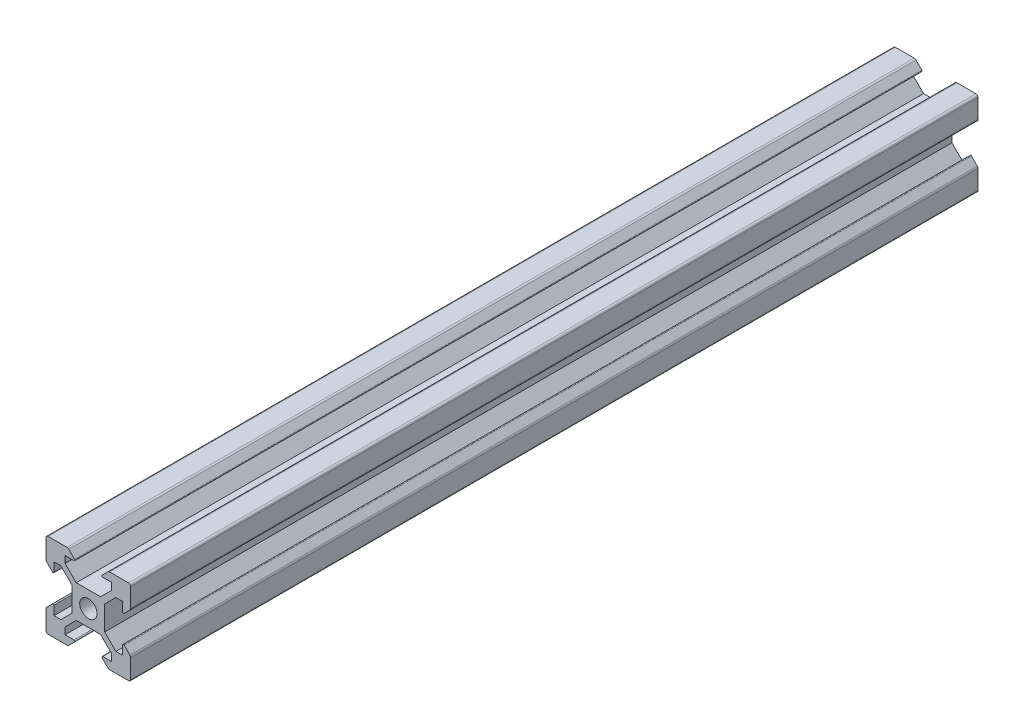
SolidWorks part; units mm, degrees
material "6063-T5"
ref_plane "Front Plane" through (0, 0, 0) normal (1, 0, 0) x (0, 1, 0)
ref_plane "Top Plane" through (0, 0, 0) normal (0, 0, 1) x (0, 1, 0)
ref_plane "Right Plane" through (0, 0, 0) normal (0, 1, 0) x (-1, 0, 0)
sketch "Sketch1" plane through (0, 0, 0) normal (0, 0, 1) x (0, 1, 0)
  line L0 (0, 0) -> (-10, 10) construction
  line L5 (-2.8601, -3.85) -> (2.8601, -3.85)
  line L6 (-3.85, -2.8601) -> (-3.85, 2.8601)
  line L11 (-2.8601, 3.85) -> (2.8601, 3.85)
  line L12 (3.85, -2.8601) -> (3.85, 2.8601)
  line L15 (-9.5, 10) -> (-5.0485, 10)
  line L16 (-4.6243, 9.8243) -> (-3.2414, 8.4414)
  line L17 (-3.3828, 8.1) -> (-5.5, 8.1)
  line L18 (-5.5, 8.1) -> (-5.5, 6.4899)
  line L19 (-5.5, 6.4899) -> (-2.8601, 3.85)
  line L20 (-6.4899, 5.5) -> (-3.85, 2.8601)
  line L21 (-10, 9.5) -> (-10, 5.0485)
  line L22 (-8.1, 5.5) -> (-6.4899, 5.5)
  line L23 (-8.1, 3.3828) -> (-8.1, 5.5)
  line L24 (-9.8243, 4.6243) -> (-8.4414, 3.2414)
  line L25 (10, 9.5) -> (10, 5.0485)
  line L26 (9.8243, 4.6243) -> (8.4414, 3.2414)
  line L27 (8.1, 3.3828) -> (8.1, 5.5)
  line L28 (8.1, 5.5) -> (6.4899, 5.5)
  line L29 (6.4899, 5.5) -> (3.85, 2.8601)
  line L30 (5.5, 6.4899) -> (2.8601, 3.85)
  line L31 (9.5, 10) -> (5.0485, 10)
  line L32 (5.5, 8.1) -> (5.5, 6.4899)
  line L33 (3.3828, 8.1) -> (5.5, 8.1)
  line L34 (4.6243, 9.8243) -> (3.2414, 8.4414)
  line L35 (9.5, -10) -> (5.0485, -10)
  line L36 (4.6243, -9.8243) -> (3.2414, -8.4414)
  line L37 (3.3828, -8.1) -> (5.5, -8.1)
  line L38 (5.5, -8.1) -> (5.5, -6.4899)
  line L39 (5.5, -6.4899) -> (2.8601, -3.85)
  line L40 (6.4899, -5.5) -> (3.85, -2.8601)
  line L41 (10, -9.5) -> (10, -5.0485)
  line L42 (8.1, -5.5) -> (6.4899, -5.5)
  line L43 (8.1, -3.3828) -> (8.1, -5.5)
  line L44 (9.8243, -4.6243) -> (8.4414, -3.2414)
  line L45 (-10, -9.5) -> (-10, -5.0485)
  line L46 (-9.8243, -4.6243) -> (-8.4414, -3.2414)
  line L47 (-8.1, -3.3828) -> (-8.1, -5.5)
  line L48 (-8.1, -5.5) -> (-6.4899, -5.5)
  line L49 (-6.4899, -5.5) -> (-3.85, -2.8601)
  line L50 (-5.5, -6.4899) -> (-2.8601, -3.85)
  line L51 (-9.5, -10) -> (-5.0485, -10)
  line L52 (-5.5, -8.1) -> (-5.5, -6.4899)
  line L53 (-3.3828, -8.1) -> (-5.5, -8.1)
  line L54 (-4.6243, -9.8243) -> (-3.2414, -8.4414)
  circle A1 centre (0, 0) radius 2.05
  arc A2 (-10, -9.5) -> (-9.5, -10) centre (-9.5, -9.5) ccw
  arc A3 (9.5, -10) -> (10, -9.5) centre (9.5, -9.5) ccw
  arc A4 (10, 9.5) -> (9.5, 10) centre (9.5, 9.5) ccw
  arc A5 (-10, 9.5) -> (-9.5, 10) centre (-9.5, 9.5) cw
  arc A6 (-3.2414, 8.4414) -> (-3.3828, 8.1) centre (-3.3828, 8.3) cw
  arc A7 (3.3828, 8.1) -> (3.2414, 8.4414) centre (3.3828, 8.3) cw
  arc A8 (8.4414, 3.2414) -> (8.1, 3.3828) centre (8.3, 3.3828) cw
  arc A9 (8.1, -3.3828) -> (8.4414, -3.2414) centre (8.3, -3.3828) cw
  arc A10 (3.2414, -8.4414) -> (3.3828, -8.1) centre (3.3828, -8.3) cw
  arc A11 (-3.3828, -8.1) -> (-3.2414, -8.4414) centre (-3.3828, -8.3) cw
  arc A12 (-8.4414, -3.2414) -> (-8.1, -3.3828) centre (-8.3, -3.3828) cw
  arc A13 (-8.1, 3.3828) -> (-8.4414, 3.2414) centre (-8.3, 3.3828) cw
  arc A14 (5.0485, 10) -> (4.6243, 9.8243) centre (5.0485, 9.4) ccw
  arc A15 (10, 5.0485) -> (9.8243, 4.6243) centre (9.4, 5.0485) cw
  arc A16 (10, -5.0485) -> (9.8243, -4.6243) centre (9.4, -5.0485) ccw
  arc A17 (5.0485, -10) -> (4.6243, -9.8243) centre (5.0485, -9.4) cw
  arc A18 (-5.0485, -10) -> (-4.6243, -9.8243) centre (-5.0485, -9.4) ccw
  arc A19 (-10, -5.0485) -> (-9.8243, -4.6243) centre (-9.4, -5.0485) cw
  arc A20 (-5.0485, 10) -> (-4.6243, 9.8243) centre (-5.0485, 9.4) cw
  arc A21 (-10, 5.0485) -> (-9.8243, 4.6243) centre (-9.4, 5.0485) ccw
  point P0 (0, 0)
  point P1 (4.8, -4.8)
  point P7 (0, 0)
  point P20 (0, 0)
  point P22 (3.68, 3.85)
  point P56 (0, 0)
  point P64 (-2.9, 8.1)
  point P79 (-8.1, 2.9)
  point P94 (-4.8, 10)
  point P97 (-10, 4.8)
  dimension "D3" = 7.7
  dimension "D2" = 4.1
  dimension "D9" = 0.5
  dimension "D10" = 0.2
  dimension "D11" = 0.6
  dimension "D1" = 10
  dimension "D4" = 7.1
  dimension "D5" = 1.4
  dimension "D6" = 4.5
  dimension "D7" = 1.9
  dimension "D8" = 4
extrude "Boss-Extrude1" add sketch "Sketch1" along normal blind 200
